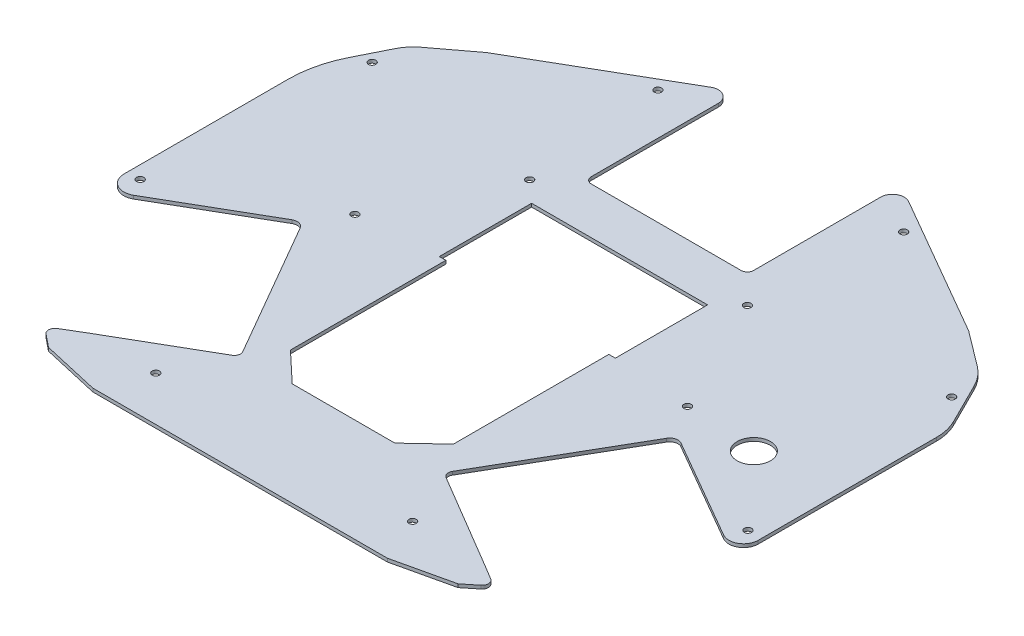
SolidWorks part; units mm, degrees
ref_plane "Front Plane" through (0, 0, 0) normal (0, 0, 1) x (1, 0, 0)
ref_plane "Top Plane" through (0, 0, 0) normal (0, 1, 0) x (1, 0, 0)
ref_plane "Right Plane" through (0, 0, 0) normal (1, 0, 0) x (0, 0, -1)
sketch "Sketch1" plane through (0, 0, 0) normal (0, 1, 0) x (1, 0, 0)
  line L0 (-31.5557, 63.2221) -> (-46.0224, 49.6064) construction
  line L5 (-46.0224, 49.6064) -> (-95.2644, 49.6064) construction
  line L6 (-95.2644, 49.6064) -> (-109.7311, 63.2221) construction
  line L7 (-109.7311, 63.2221) -> (-109.7311, 137.7742) construction
  line L8 (-112.8611, 137.7742) -> (-112.8611, 182.0493) construction
  line L9 (-112.8611, 182.0493) -> (-28.4257, 182.0493) construction
  line L10 (-28.4257, 182.0493) -> (-28.4257, 137.7742) construction
  line L11 (-31.5557, 137.7742) -> (-31.5557, 63.2221) construction
  line L12 (-31.5557, 63.2221) -> (-46.0224, 49.6064)
  line L13 (-46.0224, 49.6064) -> (-95.2644, 49.6064)
  line L14 (-95.2644, 49.6064) -> (-109.7311, 63.2221)
  line L15 (-109.7311, 63.2221) -> (-109.7311, 137.7742)
  line L16 (-112.8611, 137.7742) -> (-112.8611, 182.0493)
  line L17 (-112.8611, 182.0493) -> (-28.4257, 182.0493)
  line L18 (-28.4257, 182.0493) -> (-28.4257, 137.7742)
  line L19 (-31.5557, 137.7742) -> (-31.5557, 63.2221)
  line L20 (-109.7311, 137.7742) -> (-112.8611, 137.7742) construction
  line L21 (-109.7311, 137.7742) -> (-112.8611, 137.7742)
  line L22 (-28.4257, 137.7742) -> (-31.5557, 137.7742) construction
  line L23 (-28.4257, 137.7742) -> (-31.5557, 137.7742)
  line L24 (-70.6434, 0) -> (-70.6434, 204.3718) construction
  line L28 (24.6963, 21.4032) -> (-19.4149, 47.5637)
  line L29 (-20.4827, 51.644) -> (17.1624, 116.8472)
  line L30 (22.5258, 118.2844) -> (70.9878, 90.3048)
  line L31 (81.5046, 96.3767) -> (81.5046, 182.0252)
  line L32 (79.0144, 192.5903) -> (69.1441, 212.3646)
  line L33 (61.8119, 221.1775) -> (44.9931, 233.8542)
  line L34 (44.9931, 233.8542) -> (-23.1992, 273.2251)
  line L35 (-31.6912, 268.3222) -> (-31.6912, 207.3718)
  line L36 (-34.6912, 204.3718) -> (-106.5956, 204.3718)
  line L37 (-109.5956, 207.3718) -> (-109.5956, 268.3222)
  line L38 (-118.0876, 273.2251) -> (-186.28, 233.8542)
  line L39 (-186.28, 233.8542) -> (-204.215, 220.3362)
  line L40 (-209.8067, 213.6153) -> (-217.2476, 198.7079)
  line L41 (-222.7914, 175.1878) -> (-222.7914, 96.3767)
  line L42 (-211.6252, 89.9299) -> (-163.5124, 117.7078)
  line L43 (-158.0981, 116.257) -> (-120.4964, 51.1291)
  line L44 (-121.5945, 47.031) -> (-165.9831, 21.4032)
  line L45 (-165.9831, 21.4032) -> (-174.6764, 16.1829)
  line L46 (-175.0169, 11.2771) -> (-168.8601, 6.3045)
  line L47 (-168.8601, 6.3045) -> (-141.2868, 0)
  line L48 (-141.2868, 0) -> (0, 0)
  line L49 (0, 0) -> (27.5733, 6.3045)
  line L50 (27.5733, 6.3045) -> (33.7301, 11.2771)
  line L51 (33.3896, 16.1829) -> (24.6963, 21.4032)
  line L52 (24.6963, 21.4032) -> (-19.4149, 47.5637)
  line L53 (-20.4827, 51.644) -> (17.1624, 116.8472)
  line L54 (22.5258, 118.2844) -> (70.9878, 90.3048)
  line L55 (81.5046, 96.3767) -> (81.5046, 182.0252)
  line L56 (79.0144, 192.5903) -> (69.1441, 212.3646)
  line L57 (61.8119, 221.1775) -> (44.9931, 233.8542)
  line L58 (44.9931, 233.8542) -> (-23.1992, 273.2251)
  line L59 (-31.6912, 268.3222) -> (-31.6912, 207.3718)
  line L60 (-34.6912, 204.3718) -> (-106.5956, 204.3718)
  line L61 (-109.5956, 207.3718) -> (-109.5956, 268.3222)
  line L62 (-118.0876, 273.2251) -> (-186.28, 233.8542)
  line L63 (-186.28, 233.8542) -> (-204.215, 220.3362)
  line L64 (-209.8067, 213.6153) -> (-217.2476, 198.7079)
  line L65 (-222.7914, 175.1878) -> (-222.7914, 96.3767)
  line L66 (-211.6252, 89.9299) -> (-163.5124, 117.7078)
  line L67 (-158.0981, 116.257) -> (-120.4964, 51.1291)
  line L68 (-121.5945, 47.031) -> (-165.9831, 21.4032)
  line L69 (-165.9831, 21.4032) -> (-174.6764, 16.1829)
  line L70 (-175.0169, 11.2771) -> (-168.8601, 6.3045)
  line L71 (-168.8601, 6.3045) -> (-141.2868, 0)
  line L72 (-141.2868, 0) -> (0, 0)
  line L73 (0, 0) -> (27.5733, 6.3045)
  line L74 (27.5733, 6.3045) -> (33.7301, 11.2771)
  line L75 (33.3896, 16.1829) -> (24.6963, 21.4032)
  circle A0 centre (-123.0911, 191.3493) radius 1.75
  circle A1 centre (-216.6411, 98.0364) radius 1.75
  circle A2 centre (-18.6457, 191.3493) radius 1.75
  circle A3 centre (74.9143, 98.0364) radius 1.75
  circle A8 centre (-9.2457, 21.35) radius 1.75
  circle A9 centre (-132.4411, 21.35) radius 1.75
  circle A10 centre (-150.6414, 135.0493) radius 1.75
  circle A11 centre (8.9146, 135.0493) radius 1.75
  circle A12 centre (68.3543, 202.3493) radius 1.75
  circle A13 centre (-11.6912, 259.3718) radius 1.75
  circle A14 centre (-129.5956, 259.3718) radius 1.75
  circle A15 centre (-209.6411, 202.3493) radius 1.75
  arc A16 (-20.4827, 51.644) -> (-19.4149, 47.5637) centre (-17.8846, 50.144) ccw
  arc A17 (22.5258, 118.2844) -> (17.1624, 116.8472) centre (20.5627, 114.8841) ccw
  arc A18 (70.9878, 90.3048) -> (81.5046, 96.3767) centre (74.4934, 96.3767) ccw
  arc A19 (81.5046, 182.0252) -> (79.0144, 192.5903) centre (57.848, 182.0252) ccw
  arc A20 (69.1441, 212.3646) -> (61.8119, 221.1775) centre (46.7411, 201.1823) ccw
  arc A21 (-23.1992, 273.2251) -> (-31.6912, 268.3222) centre (-26.0299, 268.3222) ccw
  arc A22 (-34.6912, 204.3718) -> (-31.6912, 207.3718) centre (-34.6912, 207.3718) ccw
  arc A23 (-109.5956, 207.3718) -> (-106.5956, 204.3718) centre (-106.5956, 207.3718) ccw
  arc A24 (-109.5956, 268.3222) -> (-118.0876, 273.2251) centre (-115.257, 268.3222) ccw
  arc A25 (-204.215, 220.3362) -> (-209.8067, 213.6153) centre (-192.7216, 205.0873) ccw
  arc A26 (-217.2476, 198.7079) -> (-222.7914, 175.1878) centre (-170.1267, 175.1878) ccw
  arc A27 (-222.7914, 96.3767) -> (-211.6252, 89.9299) centre (-215.3473, 96.3767) ccw
  arc A28 (-158.0981, 116.257) -> (-163.5124, 117.7078) centre (-161.5306, 114.2753) ccw
  arc A29 (-121.5945, 47.031) -> (-120.4964, 51.1291) centre (-123.0945, 49.6291) ccw
  arc A30 (-174.6764, 16.1829) -> (-175.0169, 11.2771) centre (-173.132, 13.6109) ccw
  arc A31 (33.7301, 11.2771) -> (33.3896, 16.1829) centre (31.8452, 13.6109) ccw
  arc A32 (-20.4827, 51.644) -> (-19.4149, 47.5637) centre (-17.8846, 50.144) ccw
  arc A33 (22.5258, 118.2844) -> (17.1624, 116.8472) centre (20.5627, 114.8841) ccw
  arc A34 (70.9878, 90.3048) -> (81.5046, 96.3767) centre (74.4934, 96.3767) ccw
  arc A35 (81.5046, 182.0252) -> (79.0144, 192.5903) centre (57.848, 182.0252) ccw
  arc A36 (69.1441, 212.3646) -> (61.8119, 221.1775) centre (46.7411, 201.1823) ccw
  arc A37 (-23.1992, 273.2251) -> (-31.6912, 268.3222) centre (-26.0299, 268.3222) ccw
  arc A38 (-34.6912, 204.3718) -> (-31.6912, 207.3718) centre (-34.6912, 207.3718) ccw
  arc A39 (-109.5956, 207.3718) -> (-106.5956, 204.3718) centre (-106.5956, 207.3718) ccw
  arc A40 (-109.5956, 268.3222) -> (-118.0876, 273.2251) centre (-115.257, 268.3222) ccw
  arc A41 (-204.215, 220.3362) -> (-209.8067, 213.6153) centre (-192.7216, 205.0873) ccw
  arc A42 (-217.2476, 198.7079) -> (-222.7914, 175.1878) centre (-170.1267, 175.1878) ccw
  arc A43 (-222.7914, 96.3767) -> (-211.6252, 89.9299) centre (-215.3473, 96.3767) ccw
  arc A44 (-158.0981, 116.257) -> (-163.5124, 117.7078) centre (-161.5306, 114.2753) ccw
  arc A45 (-121.5945, 47.031) -> (-120.4964, 51.1291) centre (-123.0945, 49.6291) ccw
  arc A46 (-174.6764, 16.1829) -> (-175.0169, 11.2771) centre (-173.132, 13.6109) ccw
  arc A47 (33.7301, 11.2771) -> (33.3896, 16.1829) centre (31.8452, 13.6109) ccw
  dimension "D2" = 3.5
  dimension "D3" = 96.78
  dimension "D5" = 3.5
  dimension "D8" = 3.5
  dimension "D9" = 3.5
  dimension "D10" = 47
  dimension "D11" = 47
  dimension "D12" = 72.15
  dimension "D13" = 72.59
  dimension "D14" = 21.35
  dimension "D15" = 21.35
  dimension "D16" = 3.5
  dimension "D17" = 3.5
  dimension "D18" = 22.71
  dimension "D19" = 22.31
  dimension "D20" = 20
  dimension "D22" = 3.5
  dimension "D23" = 3.5
  dimension "D24" = 20
  dimension "D25" = 55
  dimension "D28" = 3.5
  dimension "D31" = 3.5
  dimension "D32" = 9.3
  dimension "D36" = 3.5
  dimension "D4" = 20.3
  dimension "D6" = 96.78
  dimension "D7" = 20.3
  dimension "D21" = 55
  dimension "D26" = 10.23
  dimension "D27" = 9.3
  dimension "D29" = 106.91
  dimension "D30" = 48.43
  dimension "D33" = 9.78
  dimension "D34" = 48.43
  dimension "D35" = 106.47
  dimension "D1" = 0
extrude "Boss-Extrude1" add sketch "Sketch1" along normal blind 1.6
sketch "Sketch2" plane through (0, 1.6, 0) normal (0, 1, 0) x (1, 0, 0)
  line L2 (81.5046, 96.3767) -> (81.5046, 182.0252) construction
  line L7 (-28.4257, 182.0493) -> (-112.8611, 182.0493) construction
  line L8 (49.9146, 158.0493) -> (74.9146, 158.0493)
  line L9 (74.9146, 158.0493) -> (74.9146, 183.0493)
  line L10 (74.9146, 183.0493) -> (49.9146, 183.0493)
  line L11 (49.9146, 183.0493) -> (49.9146, 158.0493)
  circle A1 centre (43.4146, 132.3664) radius 8.05
  circle A2 centre (40.1946, 186.7093) radius 1.75
  circle A3 centre (42.0046, 203.0493) radius 6
  dimension "D2" = 4.66
  dimension "D4" = 16.1
  dimension "D5" = 3.5
  dimension "D3" = 12
  dimension "D14" = 39.5
  dimension "D1" = 41.31
  dimension "D6" = 38.09
  dimension "D7" = 49.683
  dimension "D8" = 6.59
  dimension "D9" = 24
  dimension "D10" = 25
  dimension "D11" = 25
  dimension "D15" = 21
sketch "Sketch3" plane through (0, 1.6, 0) normal (0, 1, 0) x (1, 0, 0)
  line L0 (81.5046, 96.3767) -> (81.5046, 182.0252) construction
  line L2 (-34.6912, 204.3718) -> (-106.5956, 204.3718) construction
  circle A0 centre (43.4157, 132.3622) radius 8
  point P6 (-36.9058, 204.3718)
  dimension "D1" = 16
  dimension "D2" = 38.0889
  dimension "D3" = 72.0096
extrude "Cut-Extrude1" cut sketch "Sketch3" against normal up to surface (1.6 mm away) up to face at (-209.6411, 0, -200.5993)
